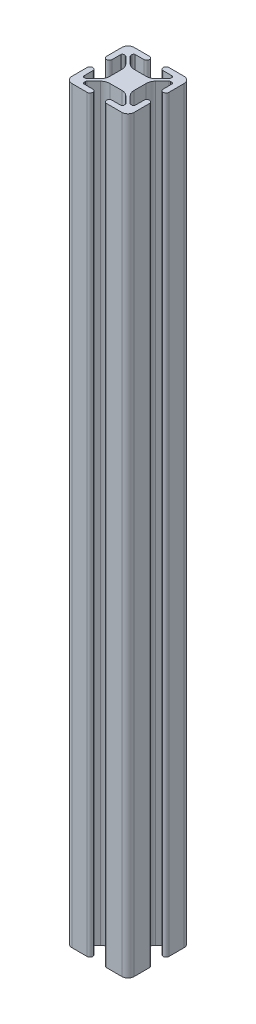
SolidWorks part; units mm, degrees
ref_plane "前视基准面" through (0, 0, 0) normal (0, 0, 1) x (1, 0, 0)
ref_plane "上视基准面" through (0, 0, 0) normal (0, 1, 0) x (1, 0, 0)
ref_plane "右视基准面" through (0, 0, 0) normal (1, 0, 0) x (0, 0, -1)
sketch "草图1" plane through (0, 0, 0) normal (0, 1, 0) x (1, 0, 0)
  line L0 (-1.0428, -10.0859) -> (3.8572, -10.0859)
  line L1 (1.0762, -11.8859) -> (3.8572, -11.8859)
  line L2 (2.8854, -15.3072) -> (0.7226, -13.1443)
  line L3 (2.1786, -16.0141) -> (0.0157, -13.8512)
  line L4 (-3.0428, -12.0859) -> (-3.0428, -16.9859)
  line L5 (-1.2428, -14.2048) -> (-1.2428, -16.9859)
  line L6 (-0.7428, -13.7048) -> (-0.3378, -13.7048)
  line L7 (0.5762, -12.3859) -> (0.5762, -12.7908)
  line L8 (-1.0428, -30.0859) -> (3.8572, -30.0859)
  line L9 (1.0762, -28.2859) -> (3.8572, -28.2859)
  line L10 (2.8854, -24.8645) -> (0.7226, -27.0274)
  line L11 (2.1786, -24.1577) -> (0.0157, -26.3205)
  line L12 (-3.0428, -28.0859) -> (-3.0428, -23.1859)
  line L13 (-1.2428, -25.9669) -> (-1.2428, -23.1859)
  line L14 (-0.7428, -26.4669) -> (-0.3378, -26.4669)
  line L15 (0.5762, -27.7859) -> (0.5762, -27.3809)
  line L16 (14.9572, -10.0859) -> (10.0572, -10.0859)
  line L17 (12.8383, -11.8859) -> (10.0572, -11.8859)
  line L18 (11.029, -15.3072) -> (13.1919, -13.1443)
  line L19 (11.7359, -16.0141) -> (13.8988, -13.8512)
  line L20 (16.9572, -12.0859) -> (16.9572, -16.9859)
  line L21 (15.1572, -14.2048) -> (15.1572, -16.9859)
  line L22 (14.6572, -13.7048) -> (14.2523, -13.7048)
  line L23 (13.3383, -12.3859) -> (13.3383, -12.7908)
  line L24 (14.9572, -30.0859) -> (10.0572, -30.0859)
  line L25 (12.8383, -28.2859) -> (10.0572, -28.2859)
  line L26 (11.029, -24.8645) -> (13.1919, -27.0274)
  line L27 (11.7359, -24.1577) -> (13.8988, -26.3205)
  line L28 (16.9572, -28.0859) -> (16.9572, -23.1859)
  line L29 (15.1572, -25.9669) -> (15.1572, -23.1859)
  line L30 (14.6572, -26.4669) -> (14.2523, -26.4669)
  line L31 (13.3383, -27.7859) -> (13.3383, -27.3809)
  line L32 (5.0068, -16.1859) -> (8.9077, -16.1859)
  line L33 (10.8572, -18.1354) -> (10.8572, -22.0363)
  line L34 (3.0572, -18.1354) -> (3.0572, -22.0363)
  line L35 (5.0068, -23.9859) -> (8.9077, -23.9859)
  circle A0 centre (6.9572, -20.0859) radius 2.5
  arc A1 (2.8854, -15.3072) -> (5.0068, -16.1859) centre (5.0068, -13.1859) ccw
  arc A2 (3.0572, -18.1354) -> (2.1786, -16.0141) centre (0.0572, -18.1354) ccw
  arc A3 (3.8572, -11.8859) -> (3.8572, -10.0859) centre (3.8572, -10.9859) ccw
  arc A4 (0.5762, -12.7908) -> (0.7226, -13.1443) centre (1.0762, -12.7908) ccw
  arc A5 (0.0157, -13.8512) -> (-0.3378, -13.7048) centre (-0.3378, -14.2048) ccw
  arc A6 (-3.0428, -16.9859) -> (-1.2428, -16.9859) centre (-2.1428, -16.9859) ccw
  arc A7 (-1.0428, -10.0859) -> (-3.0428, -12.0859) centre (-1.0428, -12.0859) ccw
  arc A8 (-0.7428, -13.7048) -> (-1.2428, -14.2048) centre (-0.7428, -14.2048) ccw
  arc A9 (1.0762, -11.8859) -> (0.5762, -12.3859) centre (1.0762, -12.3859) ccw
  arc A10 (5.0068, -23.9859) -> (2.8854, -24.8645) centre (5.0068, -26.9859) ccw
  arc A11 (2.1786, -24.1577) -> (3.0572, -22.0363) centre (0.0572, -22.0363) ccw
  arc A12 (3.8572, -30.0859) -> (3.8572, -28.2859) centre (3.8572, -29.1859) ccw
  arc A13 (0.7226, -27.0274) -> (0.5762, -27.3809) centre (1.0762, -27.3809) ccw
  arc A14 (-0.3378, -26.4669) -> (0.0157, -26.3205) centre (-0.3378, -25.9669) ccw
  arc A15 (-1.2428, -23.1859) -> (-3.0428, -23.1859) centre (-2.1428, -23.1859) ccw
  arc A16 (-3.0428, -28.0859) -> (-1.0428, -30.0859) centre (-1.0428, -28.0859) ccw
  arc A17 (-1.2428, -25.9669) -> (-0.7428, -26.4669) centre (-0.7428, -25.9669) ccw
  arc A18 (0.5762, -27.7859) -> (1.0762, -28.2859) centre (1.0762, -27.7859) ccw
  arc A19 (8.9077, -16.1859) -> (11.029, -15.3072) centre (8.9077, -13.1859) ccw
  arc A20 (11.7359, -16.0141) -> (10.8572, -18.1354) centre (13.8572, -18.1354) ccw
  arc A21 (10.0572, -10.0859) -> (10.0572, -11.8859) centre (10.0572, -10.9859) ccw
  arc A22 (13.1919, -13.1443) -> (13.3383, -12.7908) centre (12.8383, -12.7908) ccw
  arc A23 (14.2523, -13.7048) -> (13.8988, -13.8512) centre (14.2523, -14.2048) ccw
  arc A24 (15.1572, -16.9859) -> (16.9572, -16.9859) centre (16.0572, -16.9859) ccw
  arc A25 (16.9572, -12.0859) -> (14.9572, -10.0859) centre (14.9572, -12.0859) ccw
  arc A26 (15.1572, -14.2048) -> (14.6572, -13.7048) centre (14.6572, -14.2048) ccw
  arc A27 (13.3383, -12.3859) -> (12.8383, -11.8859) centre (12.8383, -12.3859) ccw
  arc A28 (11.029, -24.8645) -> (8.9077, -23.9859) centre (8.9077, -26.9859) ccw
  arc A29 (10.8572, -22.0363) -> (11.7359, -24.1577) centre (13.8572, -22.0363) ccw
  arc A30 (10.0572, -28.2859) -> (10.0572, -30.0859) centre (10.0572, -29.1859) ccw
  arc A31 (13.3383, -27.3809) -> (13.1919, -27.0274) centre (12.8383, -27.3809) ccw
  arc A32 (13.8988, -26.3205) -> (14.2523, -26.4669) centre (14.2523, -25.9669) ccw
  arc A33 (16.9572, -23.1859) -> (15.1572, -23.1859) centre (16.0572, -23.1859) ccw
  arc A34 (14.9572, -30.0859) -> (16.9572, -28.0859) centre (14.9572, -28.0859) ccw
  arc A35 (14.6572, -26.4669) -> (15.1572, -25.9669) centre (14.6572, -25.9669) ccw
  arc A36 (12.8383, -28.2859) -> (13.3383, -27.7859) centre (12.8383, -27.7859) ccw
extrude "凸台-拉伸1" add sketch "草图1" along normal blind 240 contours L3 A5 L6 A8 L5 A6 L4 A7 L0 A3 L1 A9 L7 A4 L2 A1 L32 A19 L18 A22 L23 A27 L17 A21 L16 A25 L20 A24 L21 A26 L22 A23 L19 A20 L33 A29 L27 A32 L30 A35 L29 A33 L28 A34 L24 A30 L25 A36 L31 A31 L26 A28 L35 A10 L10 A13 L15 A18 L9 A12 L8 A16 L12 A15 L13 A17 L14 A14 L11 A11 L34 A2
